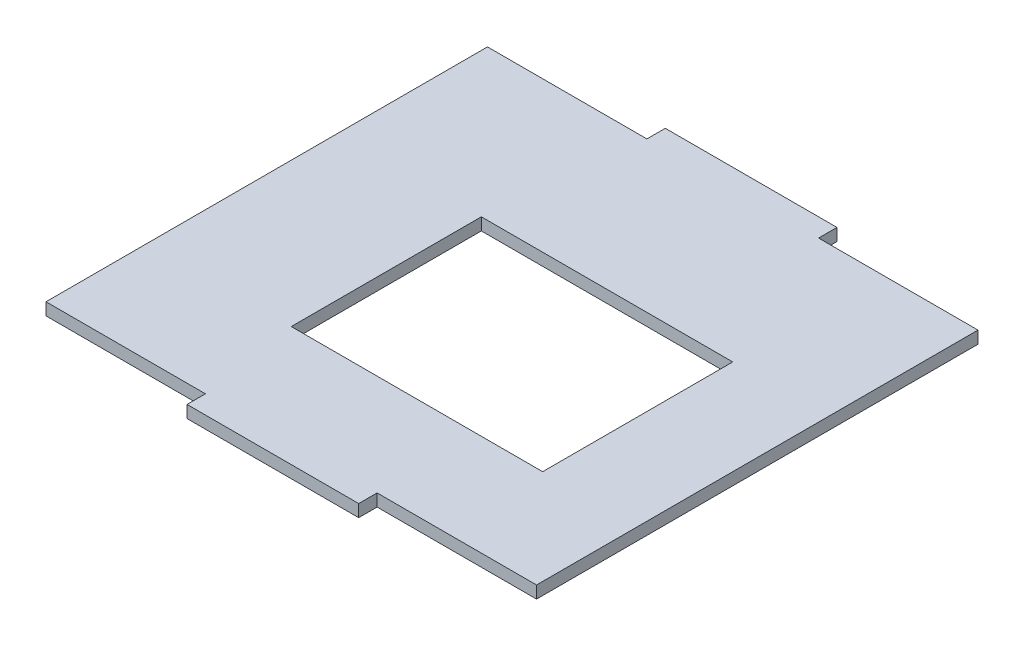
SolidWorks part; units mm, degrees
ref_plane "정면" through (0, 0, 0) normal (0, 0, 1) x (1, 0, 0)
ref_plane "윗면" through (0, 0, 0) normal (0, 1, 0) x (1, 0, 0)
ref_plane "우측면" through (0, 0, 0) normal (1, 0, 0) x (0, 0, -1)
sketch "스케치1" plane through (0, 0, 0) normal (0, 1, 0) x (1, 0, 0)
  line L1 (-21.5, 19.5) -> (21.5, 19.5)
  line L2 (-21.5, 19.5) -> (-21.5, -19.5)
  line L3 (-21.5, -19.5) -> (21.5, -19.5)
  line L4 (21.5, 19.5) -> (21.5, -19.5)
  line L5 (-21.5, 19.5) -> (21.5, -19.5) construction
  line L6 (-21.5, -19.5) -> (21.5, 19.5) construction
  point P0 (0, 0)
  dimension "D1" = 39
  dimension "D2" = 43
extrude "Top" add sketch "스케치1" along normal blind 1
sketch "스케치2" plane through (0, 1, 0) normal (0, 1, 0) x (1, 0, 0)
  line L1 (-8.25, 5.75) -> (12.25, 5.75)
  line L2 (-8.25, 5.75) -> (-8.25, -9.75)
  line L3 (-8.25, -9.75) -> (12.25, -9.75)
  line L4 (12.25, 5.75) -> (12.25, -9.75)
  line L5 (-8.25, 5.75) -> (12.25, -9.75) construction
  line L6 (-8.25, -9.75) -> (12.25, 5.75) construction
  point P0 (2, -2)
  dimension "D1" = 15.5
  dimension "D2" = 20.5
  dimension "D3" = 2
  dimension "D4" = 2
extrude "DHT22_window" cut sketch "스케치2" against normal up to next
sketch "스케치3" plane through (0, 0, 0) normal (0, -1, 0) x (1, 0, 0)
  line L0 (-20, 18) -> (-20, -18)
  line L1 (-20, -18) -> (20, -18)
  line L2 (20, -18) -> (20, 18)
  line L3 (20, 18) -> (-20, 18)
  line L4 (21.5, -19.5) -> (21.5, 19.5)
  line L5 (21.5, 19.5) -> (-21.5, 19.5)
  line L6 (-21.5, 19.5) -> (-21.5, -19.5)
  line L7 (-21.5, -19.5) -> (21.5, -19.5)
  line L8 (21.5, -19.5) -> (21.5, 19.5)
  line L9 (21.5, 19.5) -> (-21.5, 19.5)
  line L10 (-21.5, 19.5) -> (-21.5, -19.5)
  line L11 (-21.5, -19.5) -> (21.5, -19.5)
  line L13 (-7, -19.5) -> (7, -19.5)
  line L14 (-7, -19.5) -> (-7, 19.5)
  line L15 (-7, 19.5) -> (7, 19.5)
  line L16 (7, -19.5) -> (7, 19.5)
  line L17 (-7, -19.5) -> (7, 19.5) construction
  line L18 (-7, 19.5) -> (7, -19.5) construction
  point P8 (0, 0)
  line M13 (21.5, -19.5) -> (21.5, 19.5)
  line M14 (21.5, 19.5) -> (-21.5, 19.5)
  line M15 (-21.5, 19.5) -> (-21.5, -19.5)
  line M16 (-21.5, -19.5) -> (21.5, -19.5)
  dimension "D3" = 14
  dimension "D1" = 0
  dimension "D2" = 1.5
extrude "Ear" cut sketch "스케치3" against normal up to next contours L14 L1 L0 L3 L9 M16 M15 | L16 L3 L2 L1 M16 M13 M14
